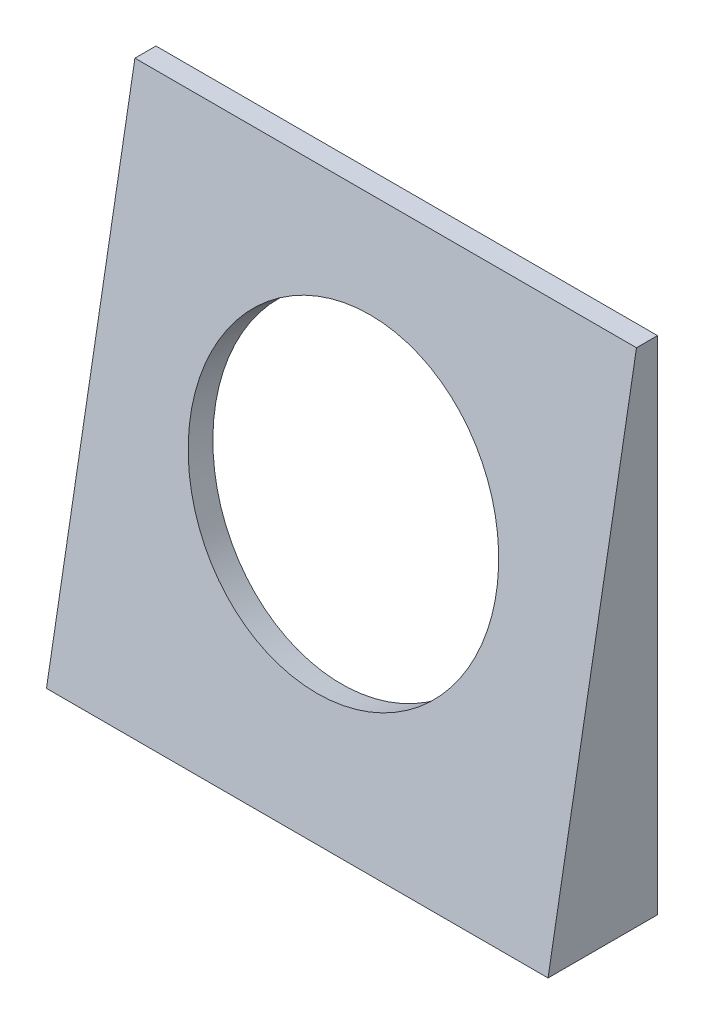
SolidWorks part; units mm, degrees
ref_plane "Front Plane" through (0, 0, 0) normal (0, 0, 1) x (1, 0, 0)
ref_plane "Top Plane" through (0, 0, 0) normal (0, 1, 0) x (1, 0, 0)
ref_plane "Right Plane" through (0, 0, 0) normal (1, 0, 0) x (0, 0, -1)
sketch "Sketch1" plane through (0, 0, 0) normal (0, 0, 1) x (1, 0, 0)
  line L1 (-10, -10) -> (10, -10)
  line L2 (-10, -10) -> (-10, 10)
  line L3 (-10, 10) -> (10, 10)
  line L4 (10, -10) -> (10, 10)
  line L5 (-10, -10) -> (10, 10) construction
  line L6 (-10, 10) -> (10, -10) construction
  line L7 (-9, -9) -> (9, -9)
  line L8 (-9, -9) -> (-9, 9)
  line L9 (-9, 9) -> (9, 9)
  line L10 (9, -9) -> (9, 9)
  line L11 (-9, -9) -> (9, 9) construction
  line L12 (-9, 9) -> (9, -9) construction
  point P0 (0, 0)
  point P6 (0, 0)
  dimension "D1" = 20
  dimension "D2" = 1
extrude "Boss-Extrude1" add sketch "Sketch1" along normal blind 10
sketch "Sketch3" plane through (10, 0, 0) normal (1, 0, 0) x (0, 0, -1)
  line L0 (0, 9) -> (-3.3502, -10)
  line L1 (-10, -10) -> (0, -10) construction
  line L2 (-3.3502, -10) -> (-4.3656, -10)
  line L3 (-4.3656, -10) -> (-1.0154, 9)
  line L5 (-1.0154, 9) -> (0, 9)
  line L6 (0, -10) -> (0, 10) construction
  dimension "D1" = 1
  dimension "D2" = 10
extrude "Boss-Extrude3" add sketch "Sketch3" against normal through all
sketch "Sketch4" plane through (-10, 0, 0) normal (-1, 0, 0) x (0, 0, 1)
  line L0 (0.8391, 10) -> (4.3656, -10)
  line L1 (10, 10) -> (0, 10) construction
  line L2 (10, -10) -> (0, -10) construction
  line L3 (4.1893, -9) -> (1.0154, 9) construction
extrude "Cut-Extrude1" cut sketch "Sketch4" against normal through all and the other way through all
sketch "Sketch5" plane through (0, 0.2714, 1.5391) normal (0, -0.1736, -0.9848) x (-1, 0, 0)
  circle A0 centre (0, 0) radius 6.1
  dimension "D1" = 12.2
extrude "Cut-Extrude2" cut sketch "Sketch5" against normal blind 10
